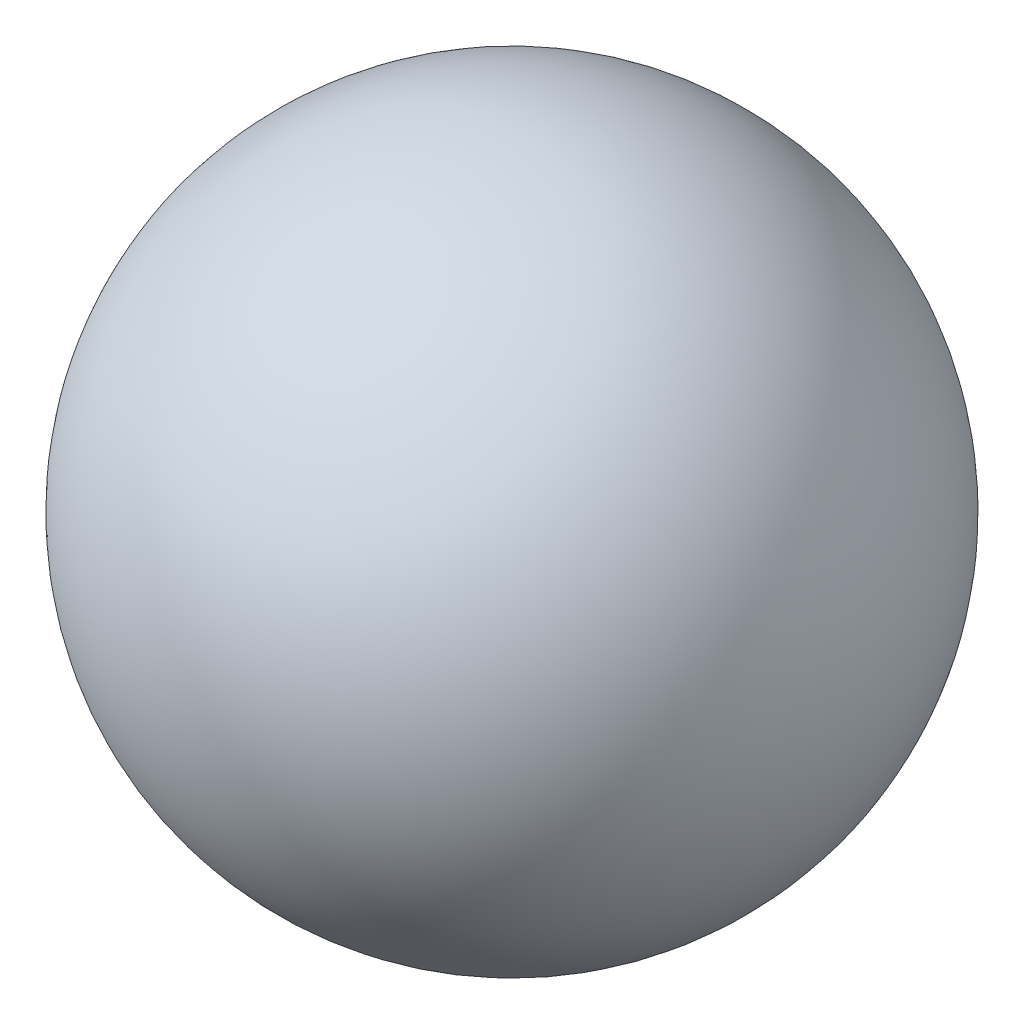
SolidWorks part; units mm, degrees
ref_plane "Front Plane" through (0, 0, 0) normal (0, 0, 1) x (1, 0, 0)
ref_plane "Top Plane" through (0, 0, 0) normal (0, 1, 0) x (1, 0, 0)
ref_plane "Right Plane" through (0, 0, 0) normal (1, 0, 0) x (0, 0, -1)
sketch "Sketch2" plane through (0, 0, 0) normal (0, 0, 1) x (1, 0, 0)
  line L0 (-12, 0) -> (12, 0)
  arc A1 (-12, 0) -> (12, 0) centre (0, 0) ccw
  point P4 (0, 0)
  dimension "D1" = 24
revolve "Revolve2" add sketch "Sketch2" angle 360 about L0
